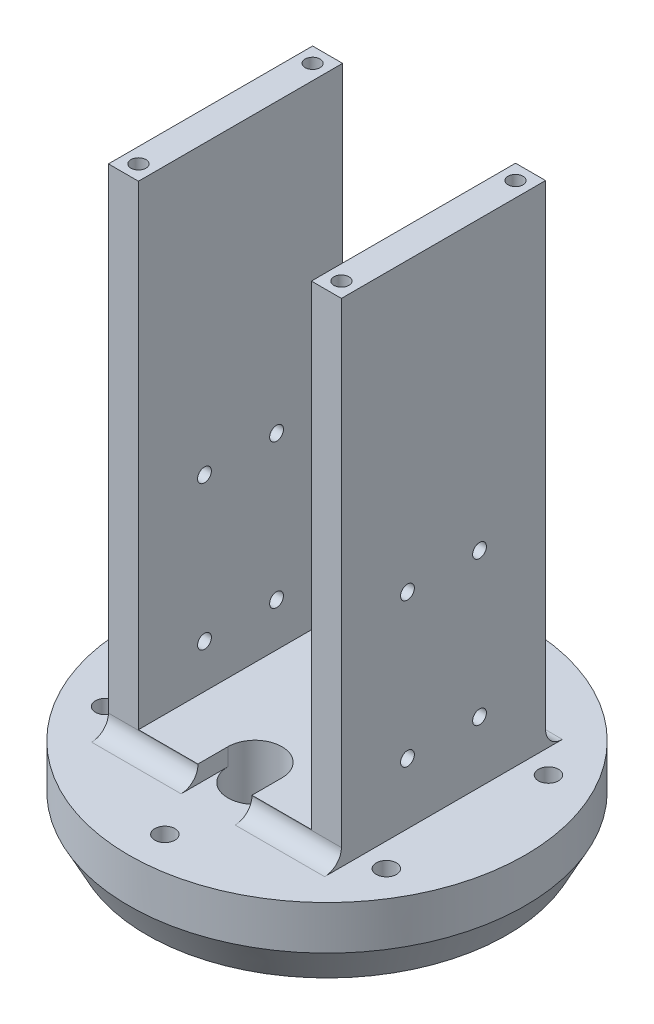
SolidWorks part; units mm, degrees
ref_plane "Alzado" through (0, 0, 0) normal (0, 0, 1) x (1, 0, 0)
ref_plane "Planta" through (0, 0, 0) normal (0, 1, 0) x (1, 0, 0)
ref_plane "Vista lateral" through (0, 0, 0) normal (1, 0, 0) x (0, 0, -1)
sketch "Croquis2" plane through (0, 0, 0) normal (0, 1, 0) x (1, 0, 0)
  circle A0 centre (0, 0) radius 33
  dimension "D1" = 66
extrude "Saliente-Extruir1" add sketch "Croquis2" along normal blind 1
sketch "Croquis3" plane through (0, 0, 0) normal (0, -1, 0) x (1, 0, 0)
  circle A0 centre (0, 0) radius 33
  circle A1 centre (0, 0) radius 27.85
  dimension "D1" = 66
  dimension "D2" = 55.7
extrude "Saliente-Extruir2" add sketch "Croquis3" along normal blind 6.3
sketch "Croquis4" plane through (0, 1, 0) normal (0, 1, 0) x (1, 0, 0)
  line L0 (0, 33) -> (0, -33) construction
  line L2 (-19.4, -17) -> (-14.4, -17)
  line L3 (-19.4, -17) -> (-19.4, 17)
  line L4 (-19.4, 17) -> (-14.4, 17)
  line L5 (-14.4, -17) -> (-14.4, 17)
  line L6 (14.4, -17) -> (19.4, -17)
  line L7 (14.4, -17) -> (14.4, 17)
  line L8 (14.4, 17) -> (19.4, 17)
  line L9 (19.4, -17) -> (19.4, 17)
  circle A0 centre (0, 0) radius 33 construction
  point P13 (-14.4, 0)
  point P14 (14.4, 0)
  dimension "D1" = 34
  dimension "D2" = 14.4
  dimension "D3" = 14.4
  dimension "D4" = 5
extrude "Saliente-Extruir3" add sketch "Croquis4" along normal blind 82
sketch "Croquis5" plane through (0, 1, 0) normal (0, 1, 0) x (1, 0, 0)
  line L1 (-14.4, 17) -> (14.4, 17)
  line L2 (-14.4, 17) -> (-14.4, -17)
  line L3 (-14.4, -17) -> (14.4, -17)
  line L4 (14.4, 17) -> (14.4, -17)
extrude "Saliente-Extruir4" add sketch "Croquis5" along normal blind 3.3
sketch "Croquis6" plane through (0, 1, 0) normal (0, 1, 0) x (1, 0, 0)
  line L0 (0, 27) -> (0, -27) construction
  circle A0 centre (0, 0) radius 27 construction
  circle A1 centre (23.3827, 13.5) radius 1.5
  circle A2 centre (0, 27) radius 1.5
  circle A3 centre (23.3827, -13.5) radius 1.5
  circle A4 centre (0, -27) radius 1.5
  circle A5 centre (-23.3827, -13.5) radius 1.5
  circle A6 centre (-23.3827, 13.5) radius 1.5
  point P18 (0, 0)
  dimension "D1" = 54
  dimension "D2" = 3
  dimension "D3" = 6
extrude "Cortar-Extruir1" cut sketch "Croquis6" against normal blind 5
fillet "Redondeo2" radius 2.8 2 edges at (0, 1, -17) (0, 1, 17)
sketch "Croquis7" plane through (0, 83, 0) normal (0, 1, 0) x (1, 0, 0)
  line L0 (19.4, 17) -> (14.4, 17) construction
  line L3 (-19.4, 17) -> (-19.4, -17) construction
  line L4 (-19.4, -17) -> (19.4, -17) construction
  circle A0 centre (16.9, 14.5) radius 1.25
  circle A1 centre (-16.9, 14.5) radius 1.25
  circle A2 centre (-16.9, -14.5) radius 1.25
  circle A3 centre (16.9, -14.5) radius 1.25
  point P11 (16.9, 17)
  dimension "D1" = 2.5
  dimension "D2" = 2.5
  dimension "D3" = 2.5
  dimension "D4" = 2.5
extrude "Cortar-Extruir2" cut sketch "Croquis7" against normal blind 10
sketch "Croquis9" plane through (0, 0, 0) normal (0, -1, 0) x (1, 0, 0)
  circle A0 centre (0, 0) radius 30
  circle A1 centre (0, 0) radius 23.65
  dimension "D1" = 60
  dimension "D2" = 47.3
extrude "Saliente-Extruir5" add sketch "Croquis9" along normal blind 12
sketch "Croquis10" plane through (0, 0, 0) normal (0, -1, 0) x (1, 0, 0)
  circle A1 centre (0, 0) radius 23.65
  circle A3 centre (0, 0) radius 23.65
  dimension "D1" = 0
extrude "Saliente-Extruir6" add sketch "Croquis10" along normal up to surface (6.3 mm away) up to face at (0, -6.3, -30)
sketch "Croquis11" plane through (0, 0, 0) normal (1, 0, 0) x (0, 0, -1)
  line L0 (33, -6.3) -> (30, -6.3)
  line L1 (30, -6.3) -> (30, -12)
  line L2 (30, -12) -> (33, -6.3)
  line L3 (0, -12) -> (0, 83) construction
  line L4 (-30, -12) -> (30, -12) construction
  line L5 (-17, 83) -> (17, 83) construction
revolve "Revolución1" add sketch "Croquis11" angle 360 about L3
sketch "Croquis12" plane through (0, -6.3, 0) normal (0, -1, 0) x (1, 0, 0)
  circle A6 centre (-0.0001, -5.5) radius 1.65
  circle A7 centre (5.5, -0.0001) radius 1.65
  circle A8 centre (-5.5, 0.0001) radius 1.65
  circle A9 centre (0.0001, 5.5) radius 1.65
  dimension "D1" = 3.3
extrude "Cortar-Extruir4" cut sketch "Croquis12" against normal blind 4
sketch "Croquis13" plane through (0, 1, 0) normal (0, 1, 0) x (1, 0, 0)
  circle A0 centre (23.3827, 13.5) radius 1.5 construction
  circle A1 centre (-23.3827, 13.5) radius 1.5
  circle A2 centre (-23.3827, 13.5) radius 1.5 construction
  circle A3 centre (23.3827, -13.5) radius 1.5 construction
  circle A4 centre (0, -27) radius 1.5 construction
  circle A5 centre (-23.3827, -13.5) radius 1.5 construction
  circle A6 centre (0, 27) radius 1.5 construction
  circle A7 centre (23.3827, 13.5) radius 1.5 construction
  circle A8 centre (23.3827, -13.5) radius 1.5 construction
  circle A9 centre (0, -27) radius 1.5 construction
  circle A10 centre (-23.3827, -13.5) radius 1.5 construction
  circle A11 centre (0, 27) radius 1.5 construction
  circle A12 centre (-23.3827, 13.5) radius 1.68
  circle A13 centre (0, 27) radius 1.68
  circle A14 centre (23.3827, 13.5) radius 1.68
  circle A15 centre (23.3827, -13.5) radius 1.68
  circle A16 centre (0, -27) radius 1.68
  circle A17 centre (-23.3827, -13.5) radius 1.68
  dimension "D1" = 0
  dimension "D2" = 0.18
extrude "Cortar-Extruir5" cut sketch "Croquis13" against normal blind 5
sketch "Croquis14" plane through (0, -6.3, 0) normal (0, -1, 0) x (1, 0, 0)
  circle A0 centre (0, 12) radius 4.5
  circle A2 centre (0.0001, 5.5) radius 1.65 construction
  point P5 (0, 0)
  point P6 (0, 0)
  dimension "D1" = 6.5
  dimension "D2" = 9
extrude "Cortar-Extruir9" cut sketch "Croquis14" against normal up to next
sketch "Croquis16" plane through (0, 4.3, 0) normal (0, 1, 0) x (1, 0, 0)
  line L8 (-14.4, -17) -> (14.4, -17)
  line L9 (14.4, -17) -> (14.4, 17)
  line L10 (14.4, 17) -> (-14.4, 17)
  line L11 (-14.4, 17) -> (-14.4, -17)
  line L15 (-14.4, -17) -> (14.4, -17)
  line L16 (14.4, -17) -> (14.4, 17)
  line L17 (14.4, 17) -> (-14.4, 17)
  line L18 (-14.4, 17) -> (-14.4, -17)
  dimension "D1" = 0
extrude "Cortar-Extruir11" cut sketch "Croquis16" against normal blind 0.4
sketch "Croquis17" plane through (0, 3.9, 0) normal (0, 1, 0) x (1, 0, 0)
  line L0 (-4.5, -12) -> (-4.5, -19.8)
  line L1 (19.4, -19.8) -> (-19.4, -19.8) construction
  line L2 (-4.5, -19.8) -> (4.5, -19.8)
  line L3 (4.5, -19.8) -> (4.5, -12)
  circle A0 centre (0, -12) radius 4.5 construction
  arc A1 (-4.5, -12) -> (4.5, -12) centre (0, -12) ccw
  dimension "D3" = 4.5
  dimension "D1" = 7.8
  dimension "D2" = 7.8
extrude "Cortar-Extruir12" cut sketch "Croquis17" against normal up to surface (2.9 mm away) up to face at (-23.3827, 1, 15.18)
sketch "Croquis18" plane through (-19.4, 0, 0) normal (-1, 0, 0) x (0, 0, 1)
  line L0 (-17, 83) -> (-17, 3.8) construction
  line L1 (-19.8, 1) -> (19.8, 1) construction
  line L2 (17, 83) -> (17, 3.8) construction
  circle A4 centre (6, 11.15) radius 1.15
  circle A5 centre (-6, 11.15) radius 1.15
  circle A6 centre (-6, 35.15) radius 1.15
  circle A7 centre (6, 35.15) radius 1.15
  point P2 (-5.6269, 10.125)
  point P8 (0, 0)
  point P11 (6.2981, 10.125)
  point P12 (0, 0)
  point P15 (0, 0)
  point P16 (0, 0)
  point P17 (-3.7511, 23.237)
  point P20 (0, 0)
  point P21 (0, 0)
  point P22 (-5.6522, 34.125)
  point P25 (6.3789, 34.125)
  dimension "D3" = 1.15
  dimension "D1" = 11
  dimension "D2" = 34.15
  dimension "D4" = 11
  dimension "D5" = 34.15
  dimension "D6" = 11
  dimension "D7" = 10.15
  dimension "D8" = 10.15
  dimension "D9" = 11
extrude "Cortar-Extruir13" cut sketch "Croquis18" against normal up to surface (38.8 mm away) up to face at (19.4, 29.0734, 0)
